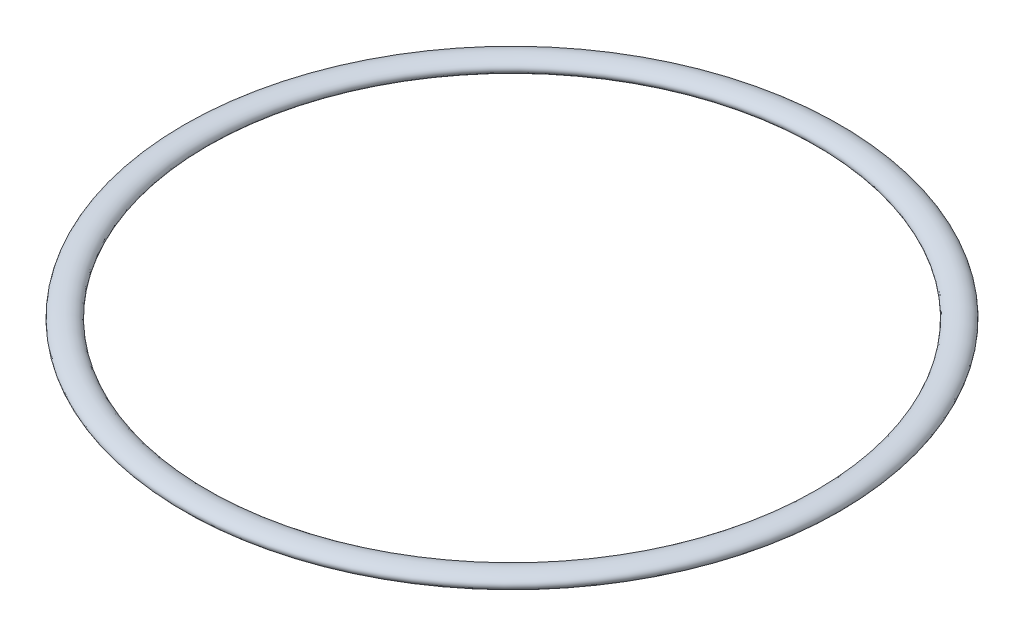
SolidWorks part; units mm, degrees
ref_plane "Front Plane" through (0, 0, 0) normal (0, 0, 1) x (1, 0, 0)
ref_plane "Top Plane" through (0, 0, 0) normal (0, 1, 0) x (1, 0, 0)
ref_plane "Right Plane" through (0, 0, 0) normal (1, 0, 0) x (0, 0, -1)
sketch "Reconstructed nominal axial profile" plane through (0, 0, 0) normal (0, 0, 1) x (1, 0, 0)
  line L0 (0, -500) -> (0, 50) construction
  ellipse E0 centre (32.425, 0) end of major axis (33.7862, 0) minor radius 0.725
revolve "Native revolved geometry" add sketch "Reconstructed nominal axial profile" angle 360 about L0
